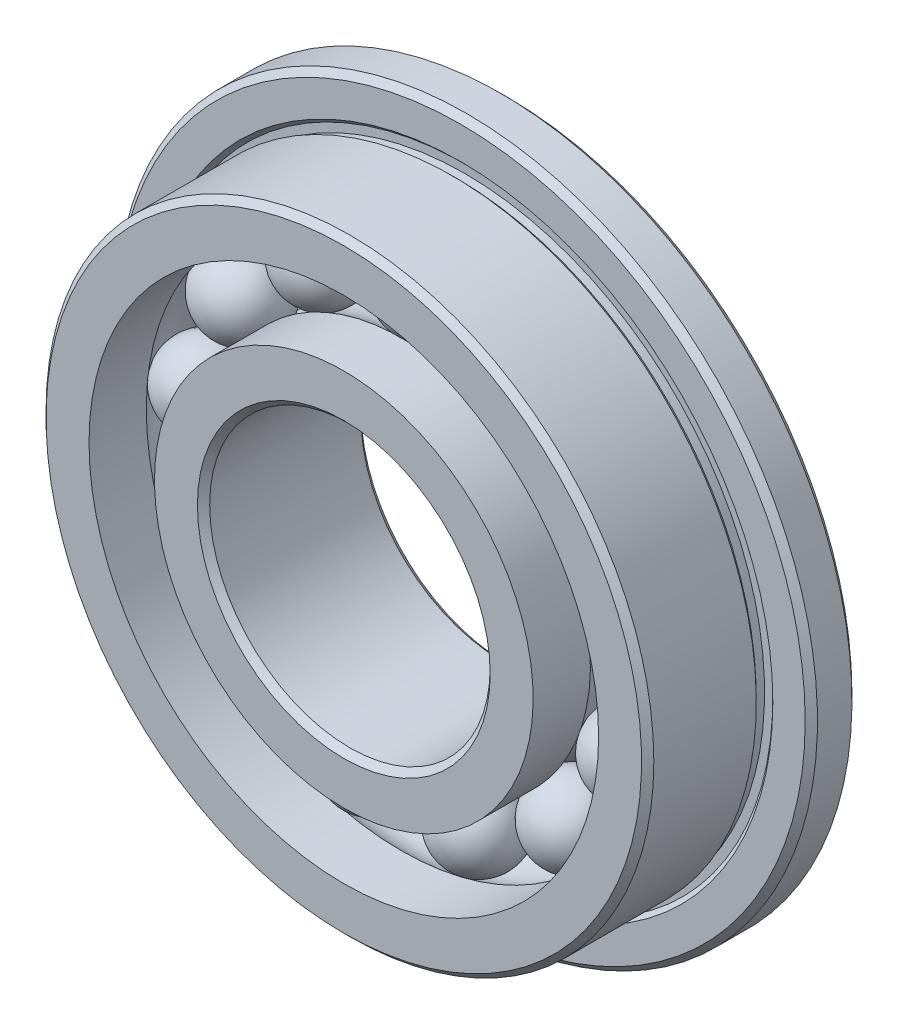
SolidWorks part; units mm, degrees
ref_plane "Front Plane" through (0, 0, 0) normal (0, 0, 1) x (1, 0, 0)
ref_plane "Top Plane" through (0, 0, 0) normal (0, 1, 0) x (1, 0, 0)
ref_plane "Right Plane" through (0, 0, 0) normal (1, 0, 0) x (0, 0, -1)
sketch "Sketch1" plane through (0, 0, 0) normal (1, 0, 0) x (0, 0, -1)
  line L0 (0, 6.5) -> (0, -6.5) construction
  line L1 (-1.75, 6.5) -> (1.75, 6.5) construction
  line L2 (0, 0) -> (1.75, 0) construction
  line L3 (1.75, 7.5) -> (1.75, -7.5) construction
  line L4 (1.75, -7.5) -> (0.75, -7.5) construction
  line L5 (1.75, 3) -> (0, 3) construction
  line L6 (1.75, 3) -> (1.75, -3) construction
  dimension "OD" = 13
  dimension "Width" = 3.5
  dimension "Flange Thickness" = 1
  dimension "ID" = 6
  dimension "Flange OD" = 15
sketch "Sketch2" plane through (0, 0, 0) normal (1, 0, 0) x (0, 0, -1)
  line L0 (1.75, 7.5) -> (0.75, 7.5)
  line L1 (0.75, 7.5) -> (0.75, 6.6768)
  line L2 (0.5732, 6.5) -> (-1.75, 6.5)
  line L3 (-1.75, 6.5) -> (-1.75, 5.45)
  line L4 (-1.75, 5.45) -> (-0.525, 5.45)
  line L5 (1.75, 7.5) -> (1.75, -7.5) construction
  line L6 (1.75, 5.45) -> (1.75, 7.5)
  line L7 (1.75, 3) -> (-1.75, 3)
  line L8 (-1.75, 3) -> (-1.75, 4.05)
  line L9 (-1.75, 4.05) -> (-0.525, 4.05)
  line L10 (1.75, 4.05) -> (1.75, 3)
  line L11 (0, 6.5) -> (0, 3) construction
  line L12 (-0.875, 4.75) -> (0.875, 4.75) construction
  line L13 (0.525, 5.45) -> (1.75, 5.45)
  line L14 (0.525, 4.05) -> (1.75, 4.05)
  line L15 (0.75, 6.6768) -> (0.8384, 6.5884)
  line L16 (0.8384, 6.5884) -> (0.8384, 6.4116)
  line L17 (0.8384, 6.4116) -> (0.6616, 6.4116)
  line L18 (0.6616, 6.4116) -> (0.5732, 6.5)
  line L19 (0.75, 6.5) -> (0.8384, 6.4116) construction
  line L20 (0.8384, 6.5884) -> (0.6616, 6.4116) construction
  line L21 (0.5732, 6.5) -> (0.75, 6.5) construction
  line L22 (0.75, 6.5) -> (0.75, 6.6768) construction
  circle A0 centre (0, 4.75) radius 0.875 construction
  arc A1 (-0.525, 5.45) -> (0.525, 5.45) centre (0, 4.75) cw
  arc A2 (-0.525, 4.05) -> (0.525, 4.05) centre (0, 4.75) ccw
  dimension "D1" = 3.5
  dimension "Ball Dia." = 1.75
  dimension "D2" = 135
  dimension "D3" = 0.25
  dimension "D4" = 1.4
  dimension "Race Thikness" = 1.05
revolve "Revolve1" add sketch "Sketch2" angle 360 about L2
fillet "Fillet1" radius 0.1313 3 edges at (0, -7.5, -1.75) (0, -7.5, -0.75) (0, -6.5, 1.75) profile chamfer
sketch "Sketch3" plane through (0, 0, 0) normal (0, 0, 1) x (1, 0, 0)
  line L0 (-3, 0) -> (3, 0) construction
  line L1 (-6.5, 0) -> (6.5, 0) construction
  point P5 (0, 0)
  dimension "ID2" = 6
  dimension "OD2" = 13
fillet "Fillet2" radius 0.1313 2 edges at (0, -3, -1.75) (0, -3, 1.75) profile chamfer
sketch "Sketch7" plane through (0, 0, 0) normal (0, 0, 1) x (1, 0, 0)
  line L0 (0, 5.625) -> (0, 3.875)
  line L1 (0, 7.5) -> (0, -7.5) construction
  line L2 (-1.0542, 5.625) -> (0, 0) construction
  line L3 (0, 0) -> (1.0542, 5.625) construction
  line L4 (1.0542, 5.625) -> (-1.0542, 5.625) construction
  circle A0 centre (0, 4.75) radius 0.875 construction
  circle A1 centre (0, 0) radius 5.625 construction
  circle A2 centre (0, 0) radius 3.875 construction
  arc A4 (0, 5.625) -> (0, 3.875) centre (0, 4.75) ccw
  dimension "D1" = 21.23
revolve "Revolve3" add sketch "Sketch7" angle 360 about L0
pattern_circular "CirPattern3" count 13 over 360 about axis through (0, 0, 0) along (0, 0, 1) of bodies 107
sketch "Sketch8" plane through (0, 0, 0) normal (1, 0, 0) x (0, 0, -1)
  line L0 (-1.75, 6.5) -> (1.75, 6.5) construction
  line L1 (1.75, 6.5) -> (1.75, 7.5) construction
  line L2 (-1.75, -6.5) -> (1.75, -6.5) construction
  line L3 (1.75, 7.5) -> (1.75, -7.5) construction
  dimension "D1" = 13
equation "\"Ball Dia.@Sketch2\" = ( \"OD@Sketch1\" - \"ID@Sketch1\" ) * .25"
equation "\"D3@Sketch2\"=\"Flange Thickness@Sketch1\"/4"
equation "\"D1@Fillet1\" = \"Race Thikness@Sketch2\" / 8"
equation "\"ID2@Sketch3\" = \"ID@Sketch1\""
equation "\"OD2@Sketch3\" = \"OD@Sketch1\""
equation "\"D1@Fillet2\" = \"Race Thikness@Sketch2\" / 8"
equation "\"D1@CirPattern3\"=360/\"D1@Sketch7\"-4"
equation "\"D4@Sketch2\" = ( \"OD@Sketch1\" - \"ID@Sketch1\" ) * .2"
